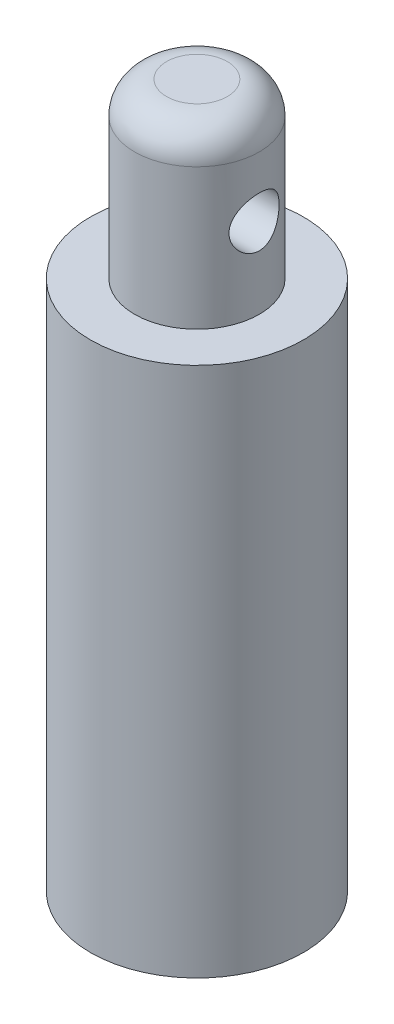
SolidWorks part; units mm, degrees
ref_plane "Front Plane" through (0, 0, 0) normal (0, 0, 1) x (1, 0, 0)
ref_plane "Top Plane" through (0, 0, 0) normal (0, 1, 0) x (1, 0, 0)
ref_plane "Right Plane" through (0, 0, 0) normal (1, 0, 0) x (0, 0, -1)
sketch "Sketch1" plane through (0, 0, 0) normal (0, 1, 0) x (1, 0, 0)
  circle A0 centre (0, 0) radius 5
  point P2 (0, 0)
  dimension "D1" = 10
extrude "Boss-Extrude1" add sketch "Sketch1" along normal blind 24.9
sketch "Sketch2" plane through (0, 24.9, 0) normal (0, 1, 0) x (1, 0, 0)
  circle A0 centre (0, 0) radius 2.925
  dimension "D1" = 5.85
extrude "Boss-Extrude2" add sketch "Sketch2" along normal offset from surface (8.1 mm away) 33 up to face at (0, 0, 5)
fillet "Fillet1" radius 1.5 1 edges at (0, 33, 2.925)
sketch "Sketch3" plane through (0, 0, 0) normal (1, 0, 0) x (0, 0, -1)
  line L0 (-5, 0) -> (5, 0) construction
  circle A0 centre (0, 28.66) radius 1.175
  dimension "D1" = 2.35
  dimension "D2" = 28.66
extrude "Cut-Extrude1" cut sketch "Sketch3" against normal through all both and the other way through all
sketch "Sketch4" plane through (0, 0, 0) normal (0, -1, 0) x (1, 0, 0)
  circle A0 centre (0, 0) radius 1.25
  dimension "D1" = 2.5
extrude "Cut-Extrude2" cut sketch "Sketch4" against normal blind 10
